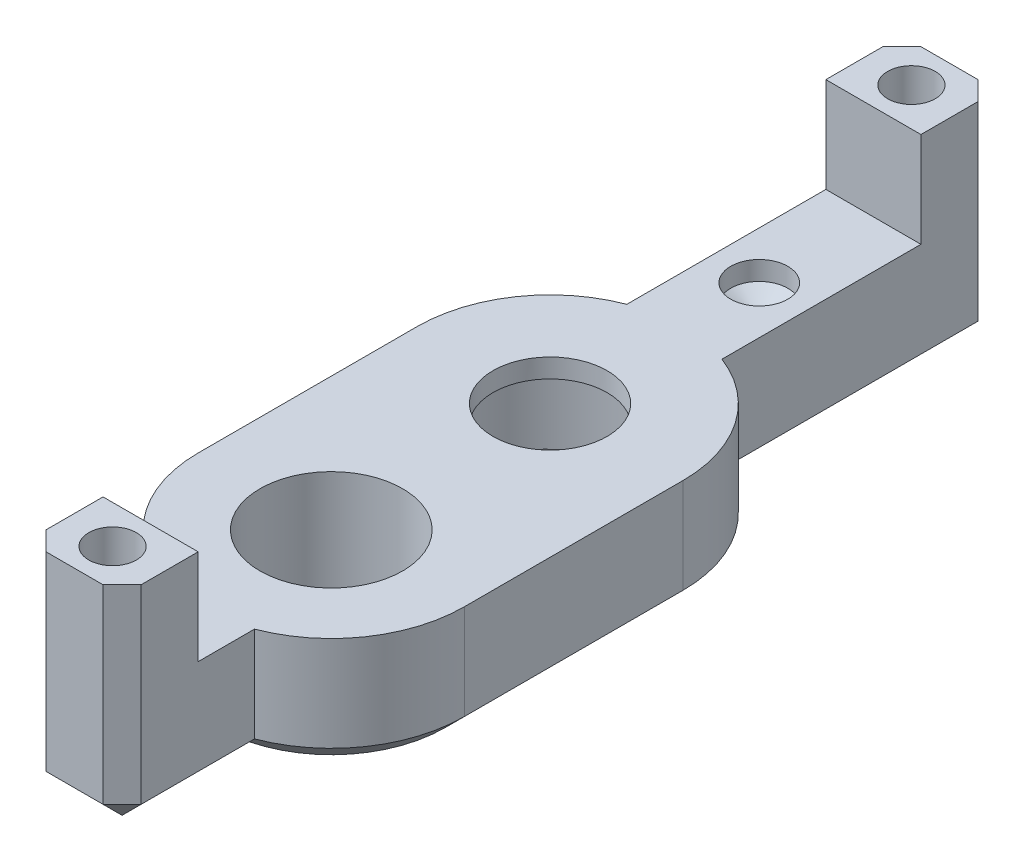
SolidWorks part; units mm, degrees
ref_plane "Plano frontal" through (0, 0, 0) normal (0, 0, 1) x (1, 0, 0)
ref_plane "Plano superior" through (0, 0, 0) normal (0, 1, 0) x (1, 0, 0)
ref_plane "Plano direito" through (0, 0, 0) normal (1, 0, 0) x (0, 0, -1)
sketch "Esboço2" plane through (0, 0, 0) normal (0, 1, 0) x (1, 0, 0)
  line L0 (0, 0) -> (0, 46)
  line L1 (0, 46) -> (14, 46)
  line L2 (14, 46) -> (14, 0)
  line L3 (14, 0) -> (0, 0)
  dimension "D1" = 46
  dimension "D2" = 14
extrude "Ressalto-extrusão1" add sketch "Esboço2" along normal blind 6
sketch "Esboço3" plane through (0, 6, 0) normal (0, 1, 0) x (1, 0, 0)
  line L0 (7, 46) -> (7, 25) construction
  line L1 (14, 46) -> (0, 46) construction
  line L2 (7, 25) -> (7, 13.5) construction
  circle A0 centre (7, 25) radius 4.6
  dimension "D3" = 9.2
  dimension "D1" = 21
  dimension "D2" = 11.5
sketch "Esboço6" plane through (0, 6, 0) normal (0, 1, 0) x (1, 0, 0)
  line L0 (4.5, 46) -> (9.5, 46) construction
  line L1 (14, 46) -> (0, 46) construction
  line L2 (4.5, 46) -> (4.5, 31.5383)
  line L3 (9.5, 46) -> (9.5, 31.5383)
  line L4 (4.5, 46) -> (0, 46)
  line L5 (0, 46) -> (0, 25)
  line L6 (0, 46) -> (0, 0) construction
  line L7 (9.5, 46) -> (14, 46)
  line L8 (14, 46) -> (14, 25)
  line L9 (14, 0) -> (14, 46) construction
  arc A0 (14, 25) -> (9.5, 31.5383) centre (7, 25) ccw
  arc A1 (4.5, 31.5383) -> (0, 25) centre (7, 25) ccw
  point P9 (7, 46)
  dimension "D2" = 5
extrude "Corte-extrusão1" cut sketch "Esboço6" against normal through all
hole_wizard "Furo de diâmetro Ø7.5 (7.5)1" positions "3DSketch2" profile "Esboço8" hole size "Ø7.5" standard "ISO" end condition through all
sketch3d "3DSketch2"
  point P0 (7, 6, -13.5)
sketch "Esboço8" plane through (7, 6, -13.5) normal (1, 0, 0) x (0, 0, 1)
  line L0 (0, 0) -> (0, 6)
  line L1 (0, 6) -> (3.75, 6)
  line L2 (3.75, 6) -> (3.75, 0)
  line L5 (3.75, 0) -> (0, 0)
  line L11 (0, -6.35) -> (0, 107.95) construction
  dimension "Thru Hole Dia." = 7.5
  dimension "Thru Hole Depth" = 6
sketch "Esboço9" plane through (0, 6, 0) normal (0, 1, 0) x (1, 0, 0)
  line L0 (0, 13.5) -> (0, 0)
  line L1 (0, 25) -> (0, 0) construction
  line L2 (0, 0) -> (4.5, 0)
  line L3 (4.5, 0) -> (4.5, 6.9617)
  line L4 (9.5, 0) -> (9.5, 6.9617)
  line L5 (9.5, 0) -> (14, 0)
  line L6 (14, 0) -> (14, 25) construction
  line L7 (14, 0) -> (14, 13.5)
  line L9 (0, 0) -> (14, 0) construction
  arc A0 (0, 13.5) -> (4.5, 6.9617) centre (7, 13.5) ccw
  arc A1 (9.5, 6.9617) -> (14, 13.5) centre (7, 13.5) ccw
  dimension "D1" = 5
extrude "Corte-extrusão2" cut sketch "Esboço9" against normal through all
sketch "Esboço10" plane through (0, 6, 0) normal (0, 1, 0) x (1, 0, 0)
  line L0 (9.5, 46) -> (9.5, 31.5383) construction
  line L1 (4.5, 46) -> (9.5, 46)
  line L2 (4.5, 46) -> (4.5, 42)
  line L3 (4.5, 42) -> (9.5, 42)
  line L4 (9.5, 46) -> (9.5, 42)
  line L5 (9.5, 6.9617) -> (9.5, 0) construction
  line L6 (4.5, 0) -> (9.5, 0)
  line L7 (4.5, 0) -> (4.5, 4)
  line L8 (4.5, 4) -> (9.5, 4)
  line L9 (9.5, 0) -> (9.5, 4)
  dimension "D1" = 4
  dimension "D2" = 4
extrude "Ressalto-extrusão2" add sketch "Esboço10" along normal blind 5
sketch "Esboço11" plane through (0, 11, 0) normal (0, 1, 0) x (1, 0, 0)
  line L0 (7, 46) -> (7, 44) construction
  line L1 (9.5, 46) -> (4.5, 46) construction
  line L2 (7, 46) -> (7, 25) construction
  line L3 (7, 0) -> (7, 2) construction
  line L4 (4.5, 0) -> (9.5, 0) construction
  dimension "D1" = 2
  dimension "D2" = 2
hole_wizard "Broca de rosquear para tarraxa de M31" positions "3DSketch3" profile "Esboço12" hole size "M3" standard "ISO"
sketch3d "3DSketch3"
  point P0 (7, 11, -2)
  point P3 (7, 11, -44)
sketch "Esboço12" plane through (7, 11, -2) normal (1, 0, 0) x (0, 0, 1)
  line L0 (0, 0) -> (0, 4.7511)
  line L1 (0, 4.7511) -> (1.25, 4)
  line L2 (1.25, 4) -> (1.25, 0)
  line L5 (1.25, 0) -> (0, 0)
  line L10 (0, 4.7511) -> (-1.25, 4) construction
  line L11 (0, -6.35) -> (0, 107.95) construction
  dimension "Hole Dia." = 2.5
  dimension "Hole Depth" = 4
  dimension "Drill Angle" = 118
hole_wizard "Furo de diâmetro Ø6.0 (6)1" positions "3DSketch4" profile "Esboço13" hole size "Ø6.0" standard "ISO" end condition through all
sketch3d "3DSketch4"
  point P0 (7, 6, -25)
sketch "Esboço13" plane through (7, 6, -25) normal (1, 0, 0) x (0, 0, 1)
  line L0 (0, 0) -> (0, 6)
  line L1 (0, 6) -> (3, 6)
  line L2 (3, 6) -> (3, 0)
  line L5 (3, 0) -> (0, 0)
  line L11 (0, -6.35) -> (0, 107.95) construction
  dimension "Thru Hole Dia." = 6
  dimension "Thru Hole Depth" = 6
sketch "Esboço14" plane through (0, 0, 0) normal (0, -1, 0) x (1, 0, 0)
  circle A0 centre (7, -25) radius 5.55
  dimension "D1" = 11.1
chamfer "Chanfro1" distance 1 angle 45 16 edges at (4.5, 0, -38.7692) (7, 0, -46) (9.5, 0, -38.7692) (4.5, 0, -3.4808) (7, 0, 0) (9.5, 0, -3.4808) (1.2337, 0, -28.9686) (1.2337, 0, -9.5314) (0, 0, -19.25) (12.7663, 0, -9.5314) (12.7663, 0, -28.9686) (14, 0, -19.25) (9.5, 5.5, -46) (4.5, 5.5, -46) (4.5, 5.5, 0) (9.5, 5.5, 0)
sketch "Esboço15" plane through (0, 6, 0) normal (0, 1, 0) x (1, 0, 0)
  line L0 (7, 25) -> (7, 36)
  dimension "D1" = 11
hole_wizard "Furo de diâmetro Ø3.0 (3)1" positions "3DSketch5" profile "Esboço16" hole size "Ø3.0" standard "ISO"
sketch3d "3DSketch5"
  point P0 (7, 6, -36)
sketch "Esboço16" plane through (7, 6, -36) normal (1, 0, 0) x (0, 0, 1)
  line L0 (0, 0) -> (0, 1.9013)
  line L1 (0, 1.9013) -> (1.5, 1)
  line L2 (1.5, 1) -> (1.5, 0)
  line L5 (1.5, 0) -> (0, 0)
  line L10 (0, 1.9013) -> (-1.5, 1) construction
  line L11 (0, -6.35) -> (0, 107.95) construction
  dimension "Hole Dia." = 3
  dimension "Hole Depth" = 1
  dimension "Drill Angle" = 118
sketch "Esboço17" plane through (0, 6, 0) normal (0, 1, 0) x (1, 0, 0)
  circle A0 centre (7, 25) radius 4.55
  dimension "D1" = 9.1
extrude "Corte-extrusão4" cut sketch "Esboço14" against normal blind 5
